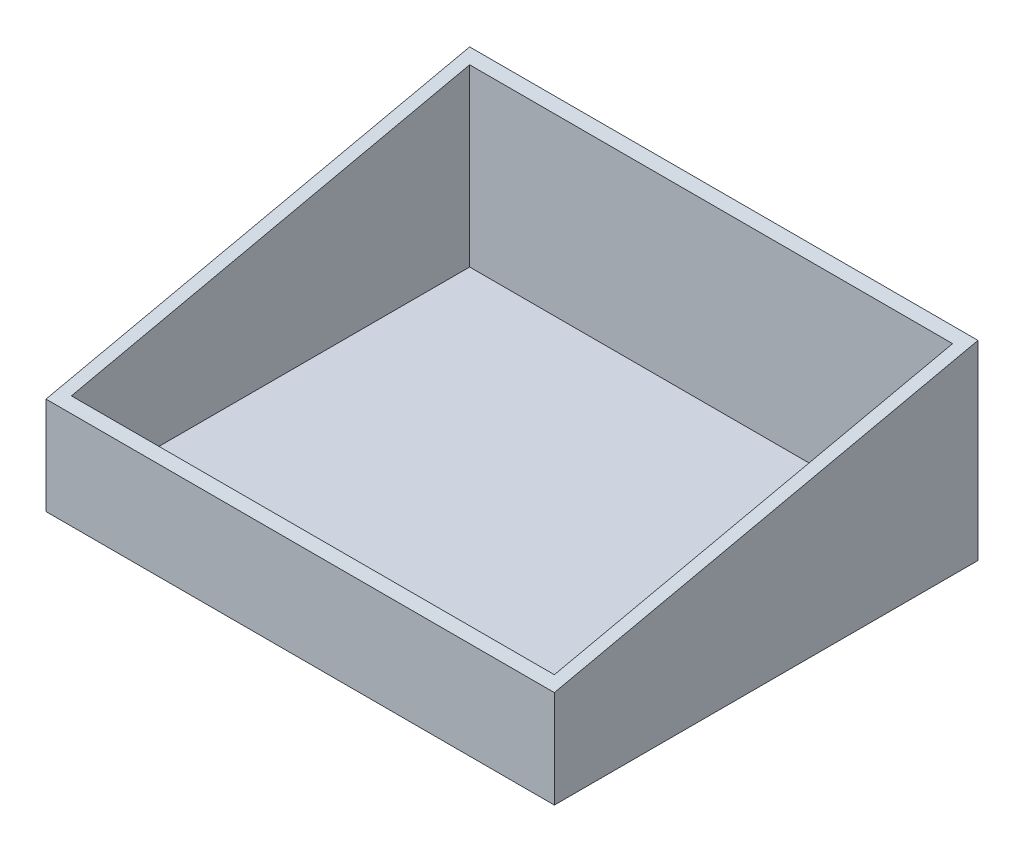
SolidWorks part; units mm, degrees
ref_plane "Front Plane" through (0, 0, 0) normal (0, 0, 1) x (1, 0, 0)
ref_plane "Top Plane" through (0, 0, 0) normal (0, 1, 0) x (1, 0, 0)
ref_plane "Right Plane" through (0, 0, 0) normal (1, 0, 0) x (0, 0, -1)
sketch "Sketch1" plane through (0, 0, 0) normal (0, 1, 0) x (1, 0, 0)
  line L1 (0, 0) -> (120, 0)
  line L2 (0, 0) -> (0, 100)
  line L3 (0, 100) -> (120, 100)
  line L4 (120, 0) -> (120, 100)
  dimension "D1" = 120
  dimension "D2" = 100
extrude "Boss-Extrude1" add sketch "Sketch1" along normal blind 45
sketch "Sketch2" plane through (120, 0, 0) normal (1, 0, 0) x (0, 0, -1)
  line L0 (0, 23) -> (0, 45)
  line L1 (0, 45) -> (0, 0) construction
  line L2 (0, 45) -> (100, 45)
  line L3 (100, 45) -> (0, 23)
  dimension "D1" = 23
extrude "Cut-Extrude1" cut sketch "Sketch2" against normal through all and the other way through all
shell "Shell1" thickness 3
